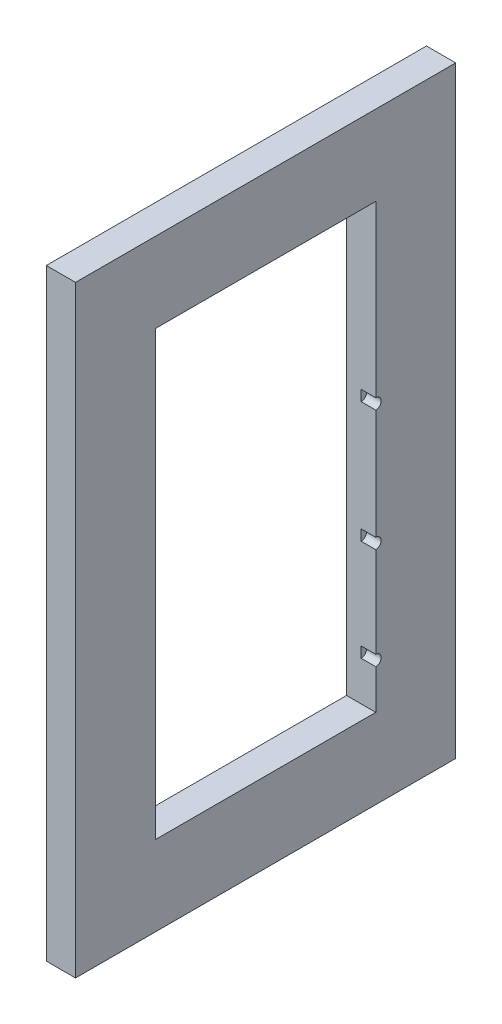
SolidWorks part; units mm, degrees
ref_plane "Alzado" through (0, 0, 0) normal (1, 0, 0) x (0, 1, 0)
ref_plane "Planta" through (0, 0, 0) normal (0, 0, 1) x (0, 1, 0)
ref_plane "Vista lateral" through (0, 0, 0) normal (0, 1, 0) x (-1, 0, 0)
sketch "Croquis1" plane through (0, 0, 0) normal (1, 0, 0) x (0, 1, 0)
  line L1 (0, 0) -> (309, 0)
  line L2 (0, 0) -> (0, 195)
  line L3 (0, 195) -> (309, 195)
  line L4 (309, 0) -> (309, 195)
  line L5 (41, 154) -> (268, 154)
  line L6 (41, 154) -> (41, 41)
  line L7 (41, 41) -> (268, 41)
  line L8 (268, 154) -> (268, 41)
  dimension "D1" = 309
  dimension "D2" = 195
  dimension "D3" = 41
  dimension "D4" = 41
  dimension "D5" = 41
  dimension "D6" = 41
extrude "Saliente-Extruir1" add sketch "Croquis1" along normal blind 15
sketch "Croquis2" plane through (15, 0, 0) normal (1, 0, 0) x (0, 1, 0)
  line L0 (0, 0) -> (309, 0) construction
  line L1 (309, 0) -> (309, 195) construction
  line L2 (309, 195) -> (0, 195) construction
  line L3 (0, 195) -> (0, 0) construction
  line L4 (0, 0) -> (309, 0)
  line L5 (309, 0) -> (309, 195)
  line L6 (309, 195) -> (0, 195)
  line L7 (0, 195) -> (0, 0)
  line L8 (41, 41) -> (268, 41) construction
  line L9 (41, 41) -> (268, 41)
  line L10 (116, 215.7868) -> (116, -27.0282) construction
  line L11 (178, 215.7868) -> (178, -27.0282) construction
  line L12 (64, 215.7868) -> (64, -27.0282) construction
  circle A0 centre (178, 41) radius 2.75
  circle A1 centre (116, 41) radius 2.75
  circle A2 centre (64, 41) radius 2.75
  point P18 (64, 41)
  dimension "D3" = 5.5
  dimension "D1" = 193
  dimension "D2" = 131
  dimension "D4" = 245
extrude "Cortar-Extruir1" cut sketch "Croquis2" against normal blind 7.5 contours L9 A2 | L9 A2 | A1 | A0
